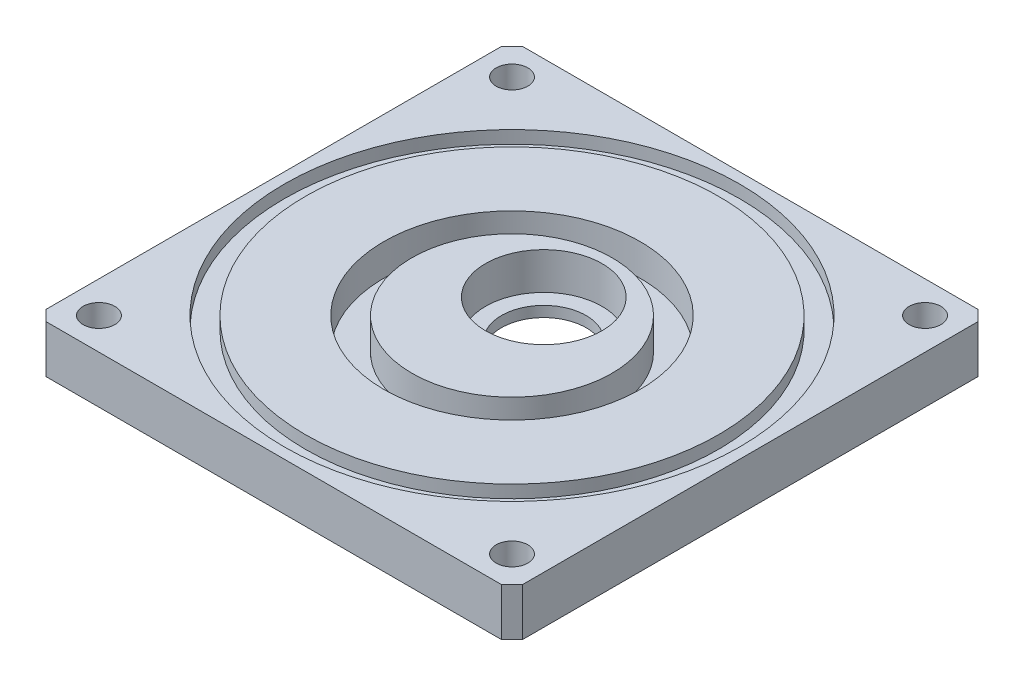
SolidWorks part; units mm, degrees
ref_plane "前视基准面" through (0, 0, 0) normal (0, 0, 1) x (1, 0, 0)
ref_plane "上视基准面" through (0, 0, 0) normal (0, 1, 0) x (1, 0, 0)
ref_plane "右视基准面" through (0, 0, 0) normal (1, 0, 0) x (0, 0, -1)
sketch "草图1" plane through (0, 0, 0) normal (0, 1, 0) x (1, 0, 0)
  line L1 (-22.5, -22.5) -> (22.5, -22.5)
  line L2 (-22.5, -22.5) -> (-22.5, 22.5)
  line L3 (-22.5, 22.5) -> (22.5, 22.5)
  line L4 (22.5, -22.5) -> (22.5, 22.5)
  line L5 (-22.5, -22.5) -> (22.5, 22.5) construction
  line L6 (-22.5, 22.5) -> (22.5, -22.5) construction
  point P0 (0, 0)
  dimension "D1" = 45
  dimension "D2" = 45
extrude "凸台-拉伸1" add sketch "草图1" along normal blind 4.5
sketch "草图2" plane through (0, 4.5, 0) normal (0, 1, 0) x (1, 0, 0)
  line L0 (0, 0) -> (0, 3) construction
  circle A0 centre (0, 3) radius 5.5
  dimension "D2" = 11
  dimension "D1" = 3
extrude "切除-拉伸1" cut sketch "草图2" against normal blind 3.5
sketch "草图3" plane through (0, 1, 0) normal (0, 1, 0) x (1, 0, 0)
  circle A0 centre (0, 3) radius 4
  dimension "D1" = 8
extrude "切除-拉伸2" cut sketch "草图3" against normal through all
sketch "草图4" plane through (0, 4.5, 0) normal (0, 1, 0) x (1, 0, 0)
  circle A0 centre (0, 0) radius 9.45
  circle A1 centre (0, 0) radius 12.1
  dimension "D1" = 18.9
  dimension "D2" = 24.2
extrude "切除-拉伸3" cut sketch "草图4" against normal blind 3
sketch "草图5" plane through (0, 4.5, 0) normal (0, 1, 0) x (1, 0, 0)
  circle A0 centre (0, 0) radius 19.5
  circle A1 centre (0, 0) radius 21.5
  dimension "D1" = 43
  dimension "D2" = 39
extrude "切除-拉伸4" cut sketch "草图5" against normal blind 1.2
chamfer "倒角1" distance 1 angle 45 4 edges at (-22.5, 2.25, 22.5) (22.5, 2.25, 22.5) (22.5, 2.25, -22.5) (-22.5, 2.25, -22.5)
sketch "草图6" plane through (0, 0, 0) normal (0, -1, 0) x (1, 0, 0)
  line L0 (0, 22.5) -> (0, -22.5) construction
  line L1 (-21.5, 22.5) -> (21.5, 22.5) construction
  line L2 (21.5, -22.5) -> (-21.5, -22.5) construction
  line L3 (-22.5, 0) -> (22.5, 0) construction
  line L4 (-22.5, -21.5) -> (-22.5, 21.5) construction
  line L5 (22.5, 21.5) -> (22.5, -21.5) construction
  circle A0 centre (-19.5, 19.5) radius 1.5
  circle A1 centre (19.5, 19.5) radius 1.5
  circle A2 centre (19.5, -19.5) radius 1.5
  circle A3 centre (-19.5, -19.5) radius 1.5
  dimension "D1" = 3
  dimension "D2" = 3
  dimension "D3" = 3
extrude "切除-拉伸5" cut sketch "草图6" against normal through all
